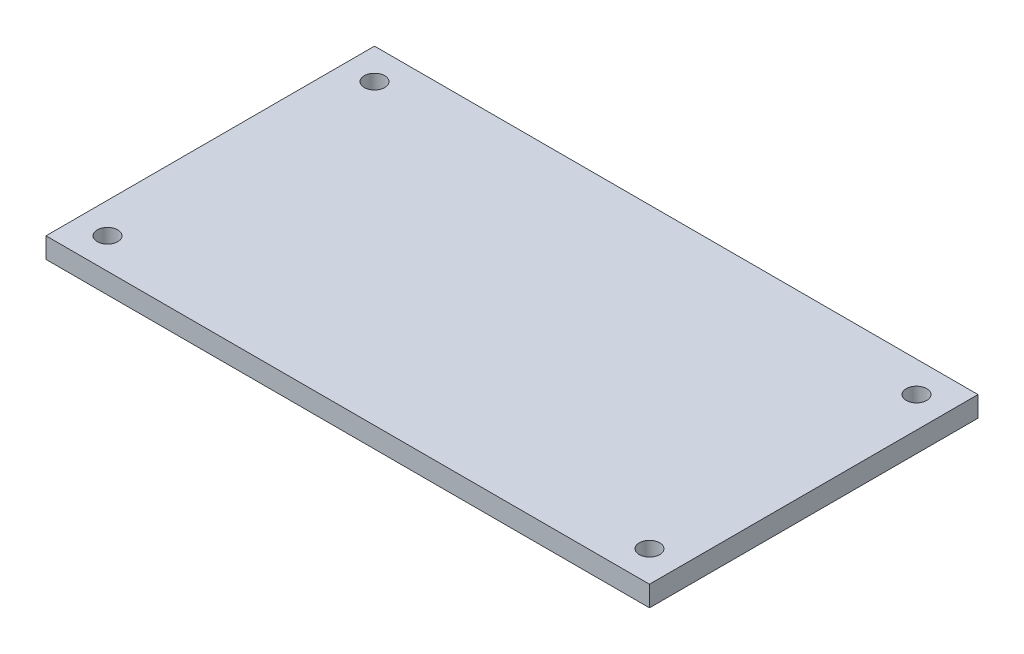
SolidWorks part; units mm, degrees
ref_plane "Front Plane" through (0, 0, 0) normal (0, 0, 1) x (1, 0, 0)
ref_plane "Top Plane" through (0, 0, 0) normal (0, 1, 0) x (1, 0, 0)
ref_plane "Right Plane" through (0, 0, 0) normal (1, 0, 0) x (0, 0, -1)
sketch "Sketch1" plane through (0, 0, 0) normal (0, 1, 0) x (1, 0, 0)
  line L1 (0, 0) -> (52.86, 0)
  line L2 (0, 0) -> (0, 26.04)
  line L3 (0, 26.04) -> (52.86, 26.04)
  line L4 (52.86, 0) -> (52.86, 26.04)
  line L5 (0, 0) -> (-3, 0)
  line L6 (0, 0) -> (0, -3)
  line L7 (0, -3) -> (-3, -3)
  line L8 (-3, 0) -> (-3, -3)
  line L9 (52.86, 26.04) -> (55.86, 26.04)
  line L10 (52.86, 26.04) -> (52.86, 29.04)
  line L11 (52.86, 29.04) -> (55.86, 29.04)
  line L12 (55.86, 26.04) -> (55.86, 29.04)
  line L13 (-3, -3) -> (55.86, -3)
  line L14 (-3, -3) -> (-3, 29.04)
  line L15 (-3, 29.04) -> (55.86, 29.04)
  line L16 (55.86, -3) -> (55.86, 29.04)
  circle A0 centre (0, 26.04) radius 1
  circle A1 centre (52.86, 26.04) radius 1
  circle A2 centre (52.86, 0) radius 1
  circle A3 centre (0, 0) radius 1
  dimension "D3" = 2
  dimension "D4" = 2
  dimension "D5" = 2
  dimension "D6" = 2
  dimension "D1" = 26.04
  dimension "D2" = 52.86
  dimension "D7" = 3
  dimension "D8" = 3
  dimension "D9" = 3
  dimension "D10" = 3
extrude "Boss-Extrude1" add sketch "Sketch1" along normal blind 2 contours A3 L6 L13 L16 L9 A1 L4 A2 L1 | A3 L2 A0 L3 A1 L10 L15 L14 L5 | A1 L9 L12 L11 L10 | A3 L1 A2 L4 A1 L3 A0 L2 | A3 L5 L8 L7 L6
